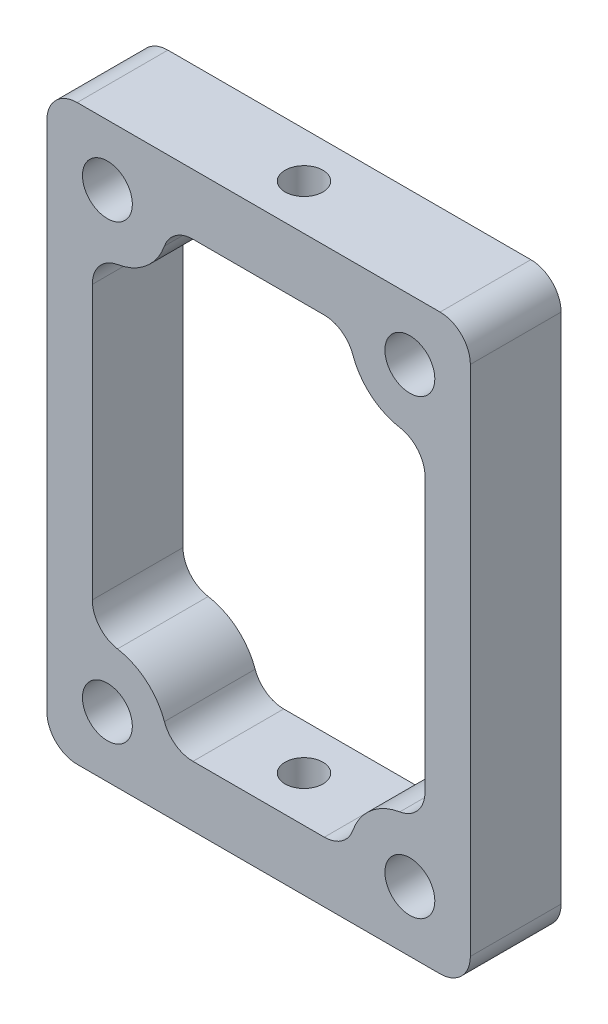
SolidWorks part; units mm, degrees
material "6061 合金"
ref_plane "前视基准面" through (0, 0, 0) normal (0, 0, 1) x (1, 0, 0)
ref_plane "上视基准面" through (0, 0, 0) normal (0, 1, 0) x (1, 0, 0)
ref_plane "右视基准面" through (0, 0, 0) normal (1, 0, 0) x (0, 0, -1)
other "Configuration Table"
sketch "草图1" plane through (0, 0, 0) normal (0, 0, 1) x (1, 0, 0)
  line L1 (-14, -18.95) -> (14, -18.95)
  line L2 (-14, -18.95) -> (-14, 18.95)
  line L3 (-14, 18.95) -> (14, 18.95)
  line L4 (14, -18.95) -> (14, 18.95)
  line L5 (-14, -18.95) -> (14, 18.95) construction
  line L6 (-14, 18.95) -> (14, -18.95) construction
  point P0 (0, 0)
  dimension "D1" = 28
  dimension "D2" = 37.9
extrude "凸台-拉伸1" add sketch "草图1" along normal mid plane 6
sketch "草图2" plane through (0, 0, 3) normal (0, 0, 1) x (1, 0, 0)
  line L0 (14, -18.95) -> (14, 18.95) construction
  line L1 (-10, -14.95) -> (10, -14.95) construction
  line L2 (-10, -14.95) -> (-10, 14.95) construction
  line L3 (-10, 14.95) -> (10, 14.95) construction
  line L4 (10, -14.95) -> (10, 14.95) construction
  line L5 (-10, -14.95) -> (10, 14.95) construction
  line L6 (-10, 14.95) -> (10, -14.95) construction
  line L7 (14, 18.95) -> (-14, 18.95) construction
  point P0 (0, 0)
  dimension "D1" = 4
  dimension "D2" = 4
hole_wizard "M4 螺纹孔1" positions "草图3" profile "草图4" tap size "M4" standard "GB" end condition through all
sketch "草图3" plane through (0, 0, 3) normal (0, 0, 1) x (1, 0, 0)
  point P0 (-10, 14.95)
  point P3 (10, 14.95)
  point P6 (10, -14.95)
  point P9 (-10, -14.95)
sketch "草图4" plane through (-10, 14.95, 3) normal (1, 0, 0) x (0, -1, 0)
  line L0 (0, 0) -> (0, 6)
  line L1 (0, 6) -> (1.65, 6)
  line L2 (1.65, 6) -> (1.65, 0)
  line L5 (1.65, 0) -> (0, 0)
  line L11 (0, -6.35) -> (0, 107.95) construction
  dimension "通孔螺纹孔钻头直径" = 3.3
  dimension "通孔螺纹孔钻头深度" = 6
cosmetic thread "孔螺蚊线1" parameters "D2"=4
cosmetic thread "孔螺蚊线2" parameters "D2"=4
cosmetic thread "孔螺蚊线3" parameters "D2"=4
cosmetic thread "孔螺蚊线4" parameters "D2"=4
sketch "草图5" plane through (0, 0, 3) normal (0, 0, 1) x (1, 0, 0)
  line L0 (14, -18.95) -> (14, 18.95) construction
  line L1 (-10, -14.95) -> (10, -14.95)
  line L2 (-10, -14.95) -> (-10, 14.95)
  line L3 (-10, 14.95) -> (10, 14.95)
  line L4 (10, -14.95) -> (10, 14.95)
  line L5 (-10, -14.95) -> (10, 14.95) construction
  line L6 (-10, 14.95) -> (10, -14.95) construction
  circle A0 centre (10, 14.95) radius 4
  circle A1 centre (-10, 14.95) radius 4
  circle A2 centre (-10, -14.95) radius 4
  circle A3 centre (10, -14.95) radius 4
  point P0 (0, 0)
extrude "切除-拉伸1" cut sketch "草图5" against normal blind 8 contours A3 L4 A0 L3 A1 L2 A2 L1
fillet "圆角1" radius 2 4 edges at (14, -18.95, 0) (-14, -18.95, 0) (-14, 18.95, 0) (14, 18.95, 0)
sketch "草图6" plane through (0, 0, 3) normal (0, 0, 1) x (1, 0, 0)
  line L0 (-11, 11.077) -> (-11, -11.077)
  line L1 (-10, -10.95) -> (-10, 10.95) construction
  line L3 (11, 11.077) -> (11, -11.077)
  line L4 (-10, 10.95) -> (-10, -10.95)
  line L5 (10, 10.95) -> (10, -10.95)
  arc A0 (-11, 11.077) -> (-10, 10.95) centre (-10, 14.95) ccw
  arc A1 (10, 10.95) -> (11, 11.077) centre (10, 14.95) ccw
  arc A2 (11, -11.077) -> (10, -10.95) centre (10, -14.95) ccw
  arc A3 (-10, -10.95) -> (-11, -11.077) centre (-10, -14.95) ccw
  arc A4 (-10, 10.95) -> (-6, 14.95) centre (-10, 14.95) ccw construction
  dimension "D1" = 1
  dimension "D2" = 1
extrude "切除-拉伸2" cut sketch "草图6" against normal blind 8
fillet "圆角3" radius 2 8 edges at (6, 14.95, 0) (11, 11.077, 0) (11, -11.077, 0) (6, -14.95, 0) (-6, -14.95, 0) (-11, -11.077, 0) (-6, 14.95, 0) (-11, 11.077, 0)
hole_wizard "M3 螺纹孔1" positions "草图8" profile "草图9" tap size "M3" standard "GB" end condition through all
sketch "草图8" plane through (0, 18.95, 0) normal (0, 1, 0) x (1, 0, 0)
  point P0 (0, 0)
sketch "草图9" plane through (0, 18.95, 0) normal (1, 0, 0) x (0, 0, 1)
  line L0 (0, 0) -> (0, 37.9)
  line L1 (0, 37.9) -> (1.25, 37.9)
  line L2 (1.25, 37.9) -> (1.25, 0)
  line L5 (1.25, 0) -> (0, 0)
  line L11 (0, -6.35) -> (0, 107.95) construction
  dimension "通孔螺纹孔钻头直径" = 2.5
  dimension "通孔螺纹孔钻头深度" = 37.9
cosmetic thread "孔螺蚊线5" parameters "D2"=3
